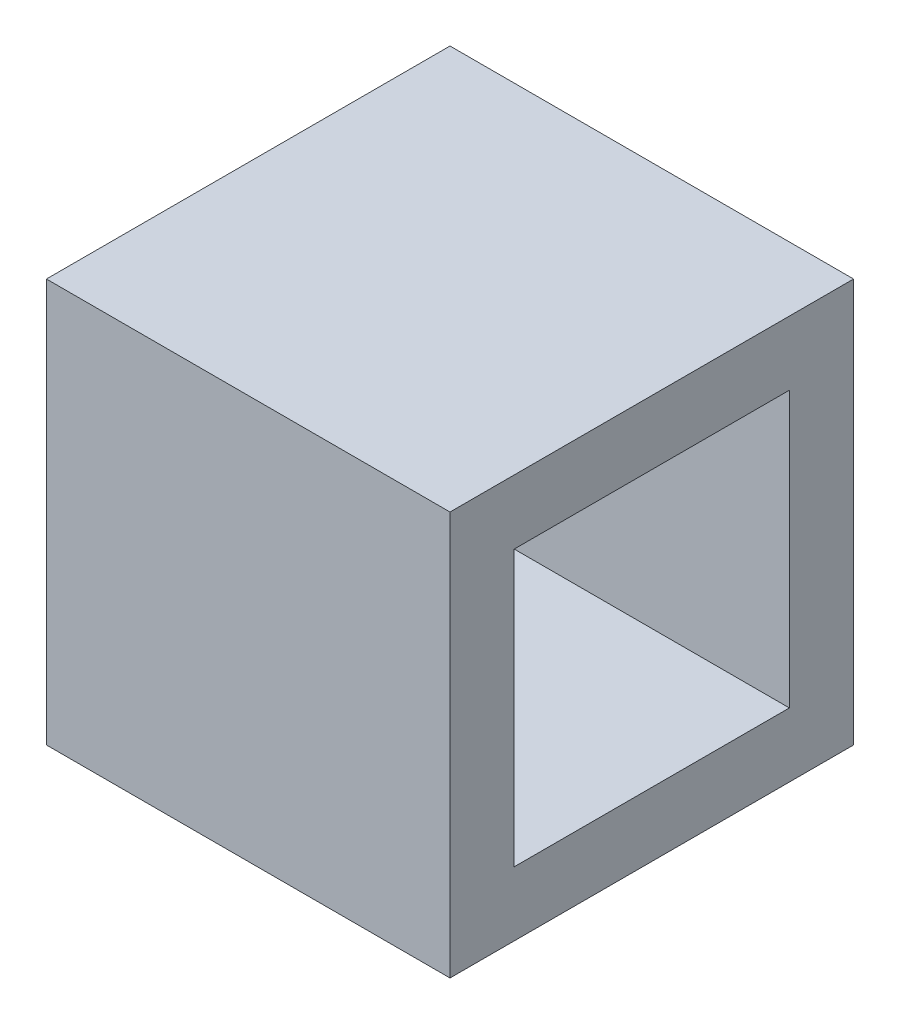
SolidWorks part; units mm, degrees
ref_plane "Front Plane" through (0, 0, 0) normal (0, 0, 1) x (1, 0, 0)
ref_plane "Top Plane" through (0, 0, 0) normal (0, 1, 0) x (1, 0, 0)
ref_plane "Right Plane" through (0, 0, 0) normal (1, 0, 0) x (0, 0, -1)
sketch "Sketch1" plane through (0, 0, 0) normal (0, 0, 1) x (1, 0, 0)
  line L1 (24.5589, 1.4668) -> (46.5589, 1.4668)
  line L2 (24.5589, 1.4668) -> (24.5589, -20.5332)
  line L3 (24.5589, -20.5332) -> (46.5589, -20.5332)
  line L4 (46.5589, 1.4668) -> (46.5589, -20.5332)
  dimension "D1" = 22
  dimension "D2" = 22
extrude "Boss-Extrude1" add sketch "Sketch1" along normal blind 22
sketch "Sketch2" plane through (46.5589, 0, 0) normal (1, 0, 0) x (0, 0, -1)
  line L0 (-22, 1.4668) -> (0, 1.4668) construction
  line L1 (-18.5, -2.0332) -> (-3.5, -2.0332)
  line L2 (-18.5, -2.0332) -> (-18.5, -17.0332)
  line L3 (-18.5, -17.0332) -> (-3.5, -17.0332)
  line L4 (-3.5, -2.0332) -> (-3.5, -17.0332)
  line L5 (0, -20.5332) -> (0, 1.4668) construction
  dimension "D1" = 15
  dimension "D2" = 3.5
  dimension "D3" = 15
  dimension "D4" = 3.5
extrude "Cut-Extrude1" cut sketch "Sketch2" against normal offset from surface (18.5 mm away) 3.5 up to face at (24.5589, -9.5332, 11)
sketch "Sketch4" plane through (0, 0, 3.5) normal (0, 0, 1) x (1, 0, 0)
  line L0 (46.5589, -20.5332) -> (46.5589, 1.4668) construction
  line L1 (46.5589, -4.0418) -> (28.0589, -4.0418)
  line L2 (46.5589, -4.0418) -> (46.5589, -4.6418)
  line L3 (46.5589, -4.6418) -> (28.0589, -4.6418)
  line L4 (28.0589, -4.0418) -> (28.0589, -4.6418)
  line L5 (28.0589, -2.0332) -> (28.0589, -17.0332) construction
  line L6 (46.5589, -9.6418) -> (28.0589, -9.6418)
  line L7 (46.5589, -9.0418) -> (28.0589, -9.0418)
  line L8 (28.0589, -9.0418) -> (28.0589, -9.6418)
  line L9 (46.5589, -9.0418) -> (46.5589, -9.6418)
  line L10 (46.5589, -14.6418) -> (28.0589, -14.6418)
  line L11 (46.5589, -14.0418) -> (28.0589, -14.0418)
  line L12 (28.0589, -14.0418) -> (28.0589, -14.6418)
  line L13 (46.5589, -14.0418) -> (46.5589, -14.6418)
  dimension "D1" = 0.6
  dimension "D2" = 3
extrude "Boss-Extrude2" [suppressed] add sketch "Sketch4" along normal blind 15
sketch "Sketch5" [suppressed] plane through (0, -14.6418, 0) normal (0, -1, 0) x (1, 0, 0)
  line L0 (28.0589, 18.5) -> (46.5589, 18.5) construction
  line L1 (28.0589, 18.5) -> (29.0589, 18.5)
  line L2 (28.0589, 18.5) -> (28.0589, 3.5)
  line L3 (28.0589, 3.5) -> (29.0589, 3.5)
  line L4 (29.0589, 18.5) -> (29.0589, 3.5)
  line L5 (28.0589, 3.5) -> (46.5589, 3.5) construction
  line L6 (28.0589, 18.5) -> (28.0589, 3.5) construction
  dimension "D1" = 1
extrude "Cut-Extrude3" [suppressed] cut sketch "Sketch5" against normal up to surface (10.6 mm away)
sketch "Sketch3" plane through (46.5589, 0, 0) normal (1, 0, 0) x (0, 0, -1)
  line L0 (-22, 1.4668) -> (0, 1.4668) construction
  line L1 (-13.6119, 1.4668) -> (1.7348, 1.4668)
  line L2 (-13.6119, 1.4668) -> (-13.6119, -21.4019)
  line L3 (-13.6119, -21.4019) -> (1.7348, -21.4019)
  line L4 (1.7348, 1.4668) -> (1.7348, -21.4019)
extrude "Cut-Extrude2" [suppressed] cut sketch "Sketch3" against normal blind 28
sketch "Sketch6" [suppressed] plane through (46.5589, 0, 0) normal (1, 0, 0) x (0, 0, -1)
  line L1 (-18.5, -14.0418) -> (-13.6119, -14.0418)
  line L2 (-18.5, -14.0418) -> (-18.5, -14.6418)
  line L3 (-18.5, -14.6418) -> (-13.6119, -14.6418)
  line L4 (-13.6119, -14.0418) -> (-13.6119, -14.6418)
  line L5 (-18.5, -4.0418) -> (-13.6119, -4.0418)
  line L6 (-18.5, -4.0418) -> (-18.5, -4.6418)
  line L7 (-18.5, -4.6418) -> (-13.6119, -4.6418)
  line L8 (-13.6119, -4.0418) -> (-13.6119, -4.6418)
extrude "Cut-Extrude4" [suppressed] cut sketch "Sketch6" against normal blind 17.5
sketch "Sketch7" plane through (0, 0, 18.5) normal (0, 0, -1) x (-1, 0, 0)
  line L0 (-46.5589, -2.0332) -> (-46.5589, -17.0332) construction
  line L1 (-46.5589, -2.7178) -> (-45.9589, -2.7178)
  line L2 (-46.5589, -2.7178) -> (-46.5589, -8.6254)
  line L3 (-46.5589, -8.6254) -> (-45.9589, -8.6254)
  line L4 (-45.9589, -2.7178) -> (-45.9589, -8.6254)
  line L5 (-46.5589, -2.0332) -> (-46.5589, -17.0332) construction
  line L6 (-46.5589, -10.2514) -> (-45.9589, -10.2514)
  line L7 (-46.5589, -10.2514) -> (-46.5589, -16.4018)
  line L8 (-46.5589, -16.4018) -> (-45.9589, -16.4018)
  line L9 (-45.9589, -10.2514) -> (-45.9589, -16.4018)
  dimension "D1" = 0.6
  dimension "D2" = 0.6
extrude "Boss-Extrude3" [suppressed] add sketch "Sketch7" along normal up to surface (4.8881 mm away)
